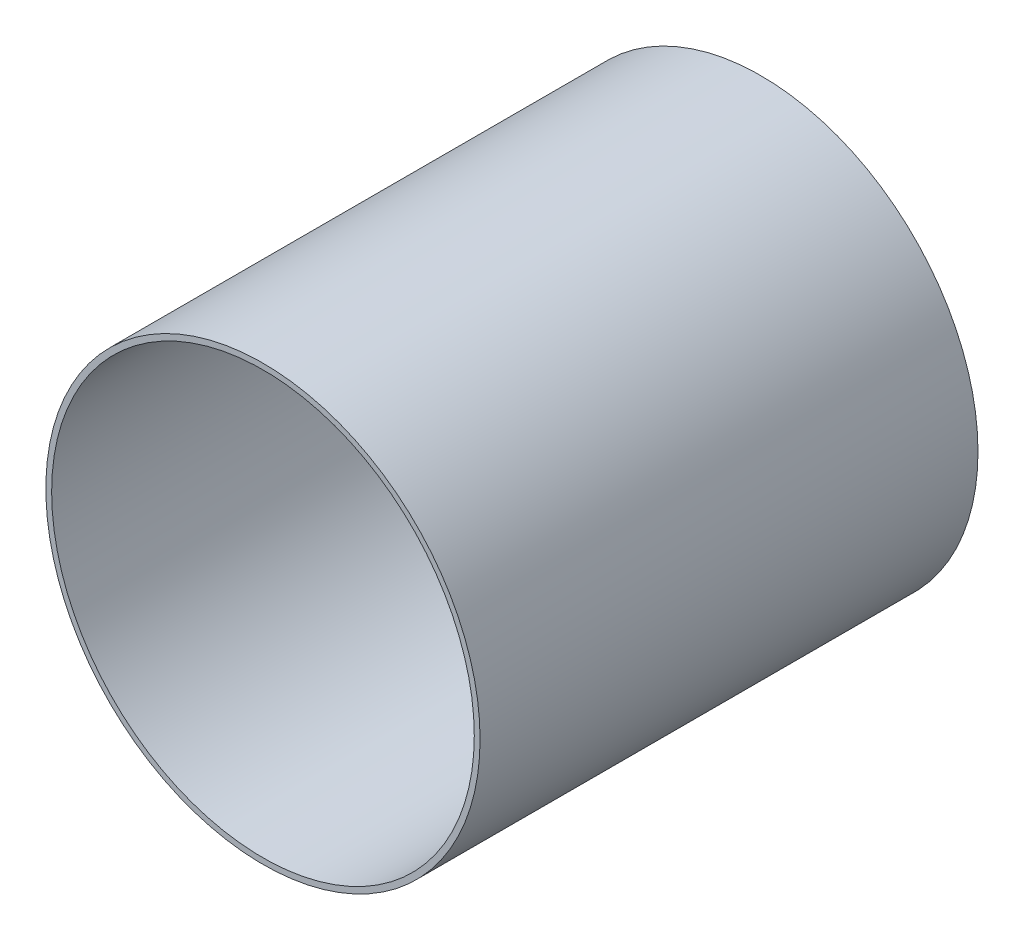
SolidWorks part; units mm, degrees
ref_plane "Front Plane" through (0, 0, 0) normal (0, 0, 1) x (1, 0, 0)
ref_plane "Top Plane" through (0, 0, 0) normal (0, 1, 0) x (1, 0, 0)
ref_plane "Right Plane" through (0, 0, 0) normal (1, 0, 0) x (0, 0, -1)
sketch "Sketch1" plane through (0, 0, 0) normal (0, 0, 1) x (1, 0, 0)
  circle A0 centre (0, 0) radius 36.5
  circle A1 centre (0, 0) radius 37.5
  dimension "D1" = 1
extrude "Boss-Extrude1" add sketch "Sketch1" along normal blind 86
